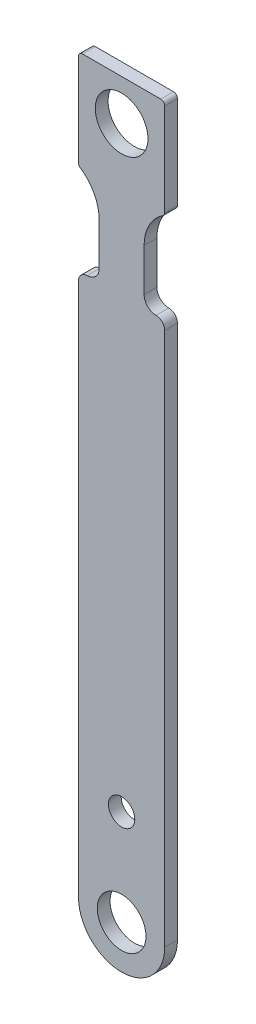
SolidWorks part; units mm, degrees
ref_plane "Front" through (0, 0, 0) normal (0, 0, 1) x (1, 0, 0)
ref_plane "Top" through (0, 0, 0) normal (0, 1, 0) x (1, 0, 0)
ref_plane "Right" through (0, 0, 0) normal (1, 0, 0) x (0, 0, -1)
sketch "草图2" plane through (0, 0, 0) normal (0, 0, 1) x (1, 0, 0)
  line L0 (2.45, 45.951) -> (-2.45, 45.951) construction
  line L1 (-2.75, 45.651) -> (-2.75, 39.8562) construction
  line L2 (-1.46, 37.442) -> (-1.46, 34.767) construction
  line L3 (-2.75, 33.467) -> (-2.75, 0) construction
  line L4 (2.75, 0) -> (2.75, 33.467) construction
  line L5 (1.46, 34.767) -> (1.46, 37.442) construction
  line L6 (2.75, 39.8562) -> (2.75, 45.651) construction
  line L7 (-2.7, 33.467) -> (-2.7, 0)
  line L8 (2.7, 0) -> (2.7, 33.467)
  line L9 (1.41, 34.767) -> (1.41, 37.442)
  line L11 (2.45, 45.901) -> (-2.45, 45.901)
  line L12 (-2.7, 45.651) -> (-2.7, 39.8562)
  line L13 (-1.41, 37.442) -> (-1.41, 34.767)
  line L14 (2.75, 39.8562) -> (2.75, 46.151) construction
  line L15 (2.7, 39.8562) -> (2.7, 46.151) construction
  line L16 (2.45, 46.451) -> (-2.45, 46.451) construction
  line L17 (2.45, 46.401) -> (-2.45, 46.401) construction
  line L18 (-2.75, 46.151) -> (-2.75, 39.8562) construction
  line L19 (-2.7, 46.151) -> (-2.7, 39.8562) construction
  line L20 (2.7, 39.8562) -> (2.7, 45.651)
  circle A0 centre (0, 0) radius 1.525
  circle A1 centre (0, 6) radius 0.825
  circle A2 centre (0, 43.351) radius 1.65
  circle A3 centre (0, 43.351) radius 1.6 construction
  circle A4 centre (0, 6) radius 1 construction
  circle A5 centre (0, 0) radius 1.51 construction
  arc A6 (2.75, 45.651) -> (2.45, 45.951) centre (2.45, 45.651) ccw construction
  arc A7 (-2.45, 45.951) -> (-2.75, 45.651) centre (-2.45, 45.651) ccw construction
  arc A8 (-2.75, 39.8562) -> (-2.6167, 39.6068) centre (-2.45, 39.8562) ccw construction
  arc A9 (-1.46, 37.442) -> (-2.6167, 39.6068) centre (-4.064, 37.442) ccw construction
  arc A10 (-2.1546, 34.067) -> (-1.46, 34.767) centre (-2.16, 34.767) ccw construction
  arc A11 (-2.1546, 34.067) -> (-2.75, 33.467) centre (-2.15, 33.467) ccw construction
  arc A12 (-2.75, 0) -> (2.75, 0) centre (0, 0) ccw construction
  arc A13 (2.75, 33.467) -> (2.1546, 34.067) centre (2.15, 33.467) ccw construction
  arc A14 (1.46, 34.767) -> (2.1546, 34.067) centre (2.16, 34.767) ccw construction
  arc A15 (2.6167, 39.6068) -> (1.46, 37.442) centre (4.064, 37.442) ccw construction
  arc A16 (2.6167, 39.6068) -> (2.75, 39.8562) centre (2.45, 39.8562) ccw construction
  arc A17 (-2.7, 0) -> (2.7, 0) centre (0, 0) ccw
  arc A18 (2.7, 33.467) -> (2.1542, 34.017) centre (2.15, 33.467) ccw
  arc A19 (1.41, 34.767) -> (2.1542, 34.017) centre (2.16, 34.767) ccw
  arc A20 (2.5889, 39.6483) -> (1.41, 37.442) centre (4.064, 37.442) ccw
  arc A21 (2.5889, 39.6483) -> (2.7, 39.8562) centre (2.45, 39.8562) ccw
  arc A22 (2.7, 45.651) -> (2.45, 45.901) centre (2.45, 45.651) ccw
  arc A23 (-2.45, 45.901) -> (-2.7, 45.651) centre (-2.45, 45.651) ccw
  arc A24 (-2.7, 39.8562) -> (-2.5889, 39.6483) centre (-2.45, 39.8562) ccw
  arc A25 (-1.41, 37.442) -> (-2.5889, 39.6483) centre (-4.064, 37.442) ccw
  arc A26 (-2.1542, 34.017) -> (-1.41, 34.767) centre (-2.16, 34.767) ccw
  arc A27 (-2.1542, 34.017) -> (-2.7, 33.467) centre (-2.15, 33.467) ccw
  arc A28 (2.75, 46.151) -> (2.45, 46.451) centre (2.45, 46.151) ccw construction
  arc A29 (2.7, 46.151) -> (2.45, 46.401) centre (2.45, 46.151) ccw construction
  arc A30 (-2.45, 46.451) -> (-2.75, 46.151) centre (-2.45, 46.151) ccw construction
  arc A31 (-2.45, 46.401) -> (-2.7, 46.151) centre (-2.45, 46.151) ccw construction
  dimension "D2" = 3.05
  dimension "D3" = 1.65
  dimension "D4" = 3.3
  dimension "D1" = 0.05
extrude "凸台-拉伸1" add sketch "草图2" along normal blind 0.8
